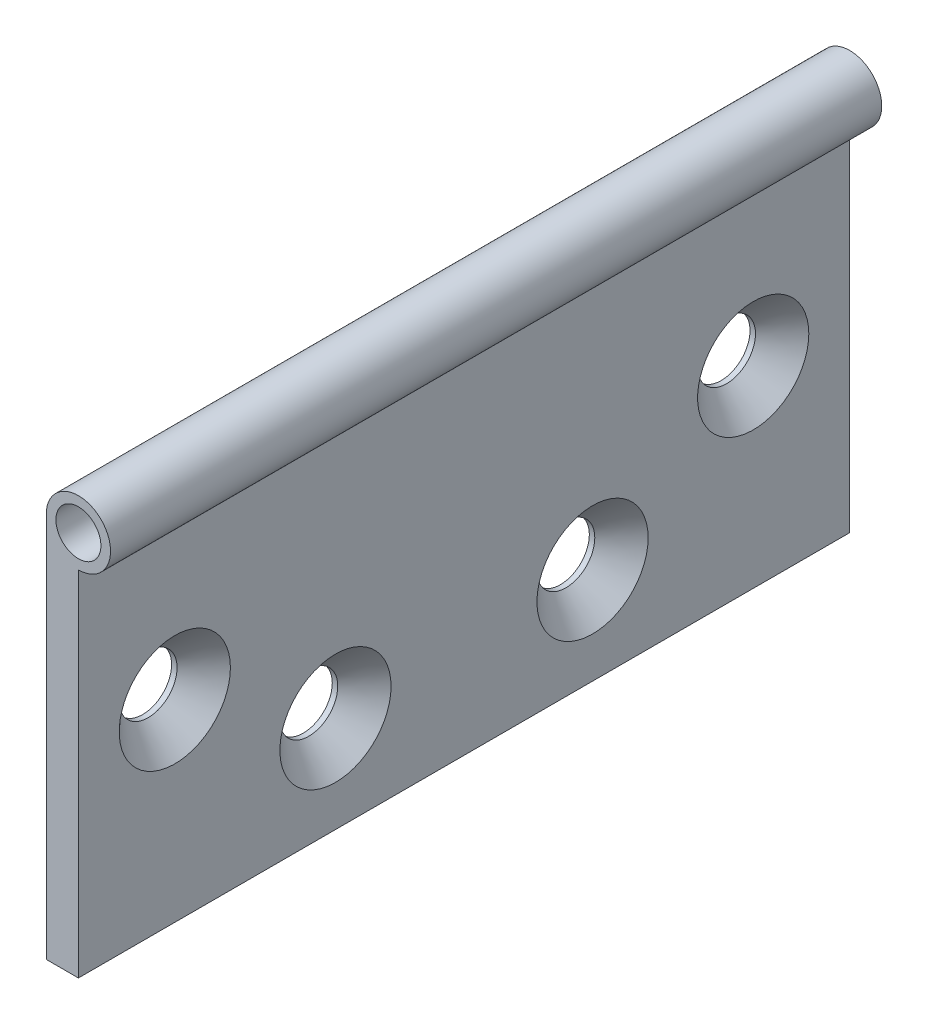
SolidWorks part; units mm, degrees
ref_plane "Front Plane" through (0, 0, 0) normal (0, 0, 1) x (1, 0, 0)
ref_plane "Top Plane" through (0, 0, 0) normal (0, 1, 0) x (1, 0, 0)
ref_plane "Right Plane" through (0, 0, 0) normal (1, 0, 0) x (0, 0, -1)
sketch "Эскиз1" plane through (0, 0, 0) normal (0, 0, 1) x (1, 0, 0)
  line L0 (0, 0) -> (0, 60)
  dimension "D1" = 60
extrude "Вытянуть-Тонкостенный1" add sketch "Эскиз1" along normal mid plane 120 thin
sketch "Эскиз2" plane through (0, 0, 60) normal (0, 0, 1) x (1, 0, 0)
  circle A0 centre (5, 60) radius 5
sweep "По траектории1" add profiles "Эскиз2" path edge at (5, 60, 0)
sketch "Эскиз4" plane through (0, 0, 60) normal (0, 0, 1) x (1, 0, 0)
  circle A0 centre (5, 60) radius 3.5
  arc A1 (5, 55) -> (0, 60) centre (5, 60) ccw construction
extrude "Вырез-Вытянуть1" cut sketch "Эскиз4" against normal through all
hole_wizard "Зенковка для  винта с плоской головкой M81" positions "Эскиз6" profile "Эскиз5" countersink size "M8" standard "Ansi Metric" end condition through all
sketch "Эскиз6" plane through (5, 0, 0) normal (1, 0, 0) x (0, 0, -1)
  point P0 (-45, 30)
  point P2 (-20, 15)
  dimension "D1" = 30
  dimension "D2" = 15
  dimension "D3" = 15
  dimension "D4" = 40
sketch "Эскиз5" plane through (5, 30, 45) normal (0, 1, 0) x (0, 0, -1)
  line L0 (0, 0) -> (0, 5)
  line L1 (0, 5) -> (4.5, 5)
  line L2 (4.5, 5) -> (4.5, 4.15)
  line L3 (4.5, 4.15) -> (8.65, 0)
  line L5 (8.65, 0) -> (0, 0)
  line L6 (-4.5, 4.15) -> (-8.65, 0) construction
  line L11 (0, -6.35) -> (0, 107.95) construction
  dimension "Диаметр сквозного отверстия" = 9
  dimension "Глубина сквозного отверстия" = 5
  dimension "Диаметр передней зенковки" = 17.3
  dimension "Угол передней зенковки" = 90
mirror "Зеркальное отражение1" about plane through (0, 0, 0) normal (0, 0, 1) of "Зенковка для  винта с плоской головкой M81"
equation "\"D1@Эскиз6\"= \"D1@Эскиз1\" / 2"
equation "\"D4@Эскиз6\"= \"D1@Вытянуть-Тонкостенный1\" / 3"
